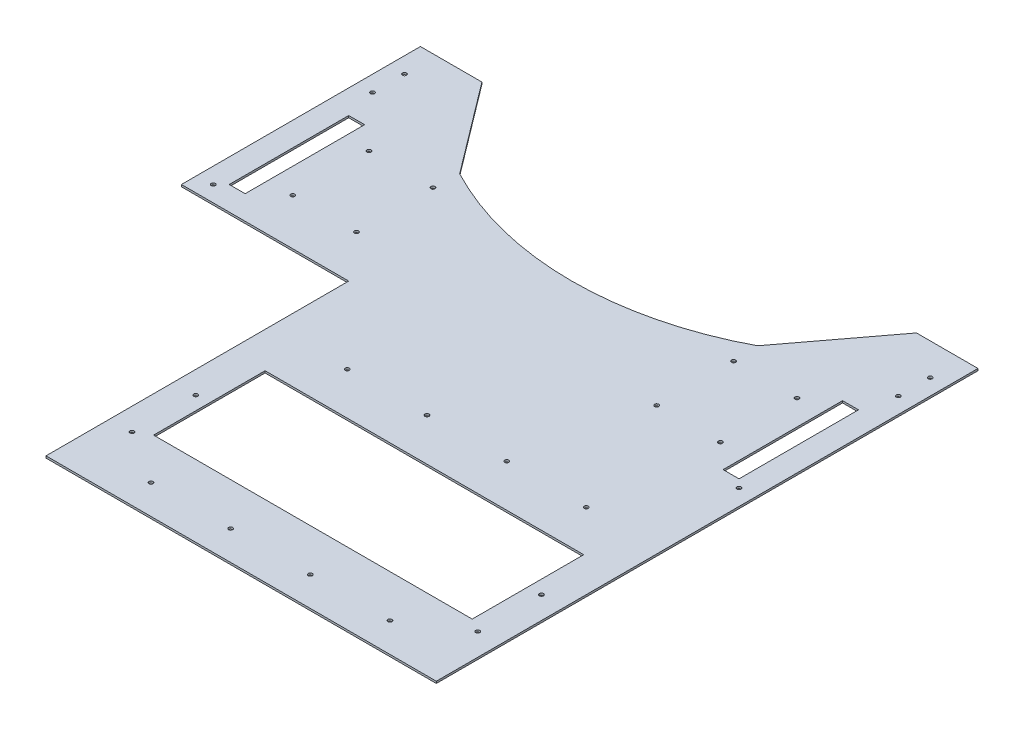
SolidWorks part; units mm, degrees
ref_plane "Front Plane" through (0, 0, 0) normal (0, 0, 1) x (1, 0, 0)
ref_plane "Top Plane" through (0, 0, 0) normal (0, 1, 0) x (1, 0, 0)
ref_plane "Right Plane" through (0, 0, 0) normal (1, 0, 0) x (0, 0, -1)
sketch "Sketch1" plane through (0, 0, 0) normal (0, 1, 0) x (1, 0, 0)
  line L0 (-444.5, 431.8) -> (-395.4569, 431.8)
  line L1 (-311.15, 0) -> (0, 0)
  line L2 (-444.5, 431.8) -> (-444.5, 241.3)
  line L3 (-395.4569, 431.8) -> (-340.9437, 359.5617)
  line L4 (-311.15, 241.3) -> (-311.15, 0)
  line L5 (0, 431.8) -> (0, 0)
  line L6 (-340.9437, 359.5617) -> (-103.5563, 359.5617) construction
  line L7 (-222.25, 359.5617) -> (-222.25, 584.8157) construction
  line L8 (-103.5563, 359.5617) -> (-49.0431, 431.8)
  line L9 (-49.0431, 431.8) -> (0, 431.8)
  line L10 (-444.5, 241.3) -> (-311.15, 241.3)
  line L11 (-282.575, 101.6317) -> (-311.15, 101.6317) construction
  line L12 (-282.575, 57.1818) -> (-28.575, 57.1817)
  line L13 (-282.575, 57.1818) -> (-282.575, 146.0817)
  line L14 (-282.575, 146.0817) -> (-28.575, 146.0817)
  line L15 (-28.575, 57.1817) -> (-28.575, 146.0817)
  line L16 (-28.575, 101.6317) -> (0, 101.6317) construction
  line L17 (-31.75, 355.6) -> (-31.75, 260.35)
  line L18 (-425.45, 355.6) -> (-412.75, 355.6)
  line L19 (-425.45, 355.6) -> (-425.45, 260.35)
  line L20 (-425.45, 260.35) -> (-412.75, 260.35)
  line L21 (-412.75, 355.6) -> (-412.75, 260.35)
  line L22 (-19.05, 260.35) -> (-31.75, 260.35)
  line L23 (-19.05, 355.6) -> (-19.05, 260.35)
  line L24 (-19.05, 355.6) -> (-31.75, 355.6)
  line L25 (-282.575, 101.6317) -> (-28.575, 101.6317) construction
  line L26 (-155.575, 57.1817) -> (-155.575, 146.0817) construction
  arc A0 (-340.9437, 359.5617) -> (-103.5563, 359.5617) centre (-222.25, 584.8157) ccw
  circle A1 centre (-250.825, 23.368) radius 1.632
  circle A2 centre (-187.325, 23.368) radius 1.632
  circle A3 centre (-187.325, 179.8955) radius 1.632
  circle A4 centre (-250.825, 179.8955) radius 1.632
  circle A5 centre (-123.825, 179.8955) radius 1.632
  circle A6 centre (-60.325, 179.8955) radius 1.632
  circle A7 centre (-123.825, 23.368) radius 1.632
  circle A8 centre (-60.325, 23.368) radius 1.6319
  line B0 (0, 457.2) -> (-457.2, 457.2) construction
  line B1 (0, 457.2) -> (0, 0) construction
  line B2 (0, 0) -> (-457.2, 0) construction
  line B3 (-457.2, 457.2) -> (-457.2, 0) construction
  line B4 (-457.2, 228.6) -> (-330.2, 228.6) construction
  line B5 (-330.2, 0) -> (-330.2, 228.6) construction
  arc B6 (-327.0888, 354.3418) -> (-120.3363, 354.3418) centre (-223.7126, 583.1293) ccw construction
  arc B7 (-327.0888, 411.3998) -> (-120.3363, 411.3998) centre (-223.7126, 182.6123) cw construction
  arc B8 (-327.0888, 354.3418) -> (-327.0888, 411.3998) centre (-314.1982, 382.8708) cw construction
  arc B9 (-120.3363, 411.3998) -> (-120.3363, 354.3418) centre (-133.2269, 382.8708) cw construction
  dimension "D14" = 63.5
  dimension "D12" = 3.2639
  dimension "D2" = 254
  dimension "D3" = 88.9
  dimension "D4" = 95.25
  dimension "D5" = 12.7
  dimension "D6" = 19.05
  dimension "D7" = 311.15
  dimension "D8" = 431.8
  dimension "D9" = 444.5
  dimension "D10" = 241.3
  dimension "D11" = 19.05
  dimension "D13" = 156.5275
  dimension "D15" = 63.5
  dimension "D16" = 23.368
sketch_block_instance "Block1-1"
sketch_block "Block1" parameters "D1"=228.6
sketch_block_instance "Block2-1"
sketch_block "Block2"
extrude "Boss-Extrude1" add sketch "Sketch1" along normal blind 1.5875 contours A0 L3 L0 L2 L10 L4 L1 L5 L9 L8 L24 L23 L22 L17 L15 L12 L13 L14 L18 L21 L20 L19
sketch "Sketch2" plane through (0, 1.5875, 0) normal (0, 1, 0) x (1, 0, 0)
  line L0 (-155.575, 57.1818) -> (-155.575, 168.0977) construction
  line L1 (-282.575, 57.1818) -> (-28.575, 57.1817) construction
  line L2 (-311.15, 0) -> (0, 0) construction
  line L3 (-311.15, 241.3) -> (-311.15, 0) construction
  circle A0 centre (-293.37, 101.6) radius 1.632
  circle A1 centre (-293.37, 50.8) radius 1.632
  circle A2 centre (-17.78, 101.6) radius 1.6319
  circle A3 centre (-17.78, 50.8) radius 1.6319
  dimension "D1" = 3.2639
  dimension "D2" = 50.8
  dimension "D3" = 50.8
  dimension "D4" = 17.78
extrude "Cut-Extrude1" cut sketch "Sketch2" against normal up to next
sketch "Sketch4" plane through (0, 1.5875, 0) normal (0, 1, 0) x (1, 0, 0)
  line L0 (-444.5, 336.55) -> (0, 336.55) construction
  line L1 (-444.5, 431.8) -> (-444.5, 241.3) construction
  line L2 (0, 431.8) -> (0, 0) construction
  line L3 (-222.25, 336.55) -> (-222.25, 422.1428) construction
  line L4 (-49.0431, 431.8) -> (0, 431.8) construction
  circle A0 centre (-102.4399, 339.3921) radius 1.6319
  circle A1 centre (-51.6403, 339.1989) radius 1.6319
  circle A2 centre (-102.5562, 278.2389) radius 1.6319
  circle A3 centre (-51.7562, 278.2389) radius 1.632
  circle A4 centre (-392.7438, 278.2389) radius 1.632
  circle A5 centre (-341.9438, 278.2389) radius 1.632
  circle A6 centre (-392.8597, 339.1989) radius 1.632
  circle A7 centre (-342.0601, 339.3921) radius 1.632
  circle A8 centre (-12.7, 406.4) radius 1.632
  circle A9 centre (-12.7, 381) radius 1.632
  circle A10 centre (-12.7, 254) radius 1.632
  circle A11 centre (-431.8, 254) radius 1.6319
  circle A12 centre (-431.8, 381) radius 1.6319
  circle A13 centre (-431.8, 406.4) radius 1.6319
  circle A14 centre (-17.78, 101.6) radius 1.6319 construction
  dimension "D1" = 25.4
  dimension "D2" = 127
  dimension "D3" = 25.4
  dimension "D4" = 12.7
extrude "Cut-Extrude2" cut sketch "Sketch4" against normal up to next
